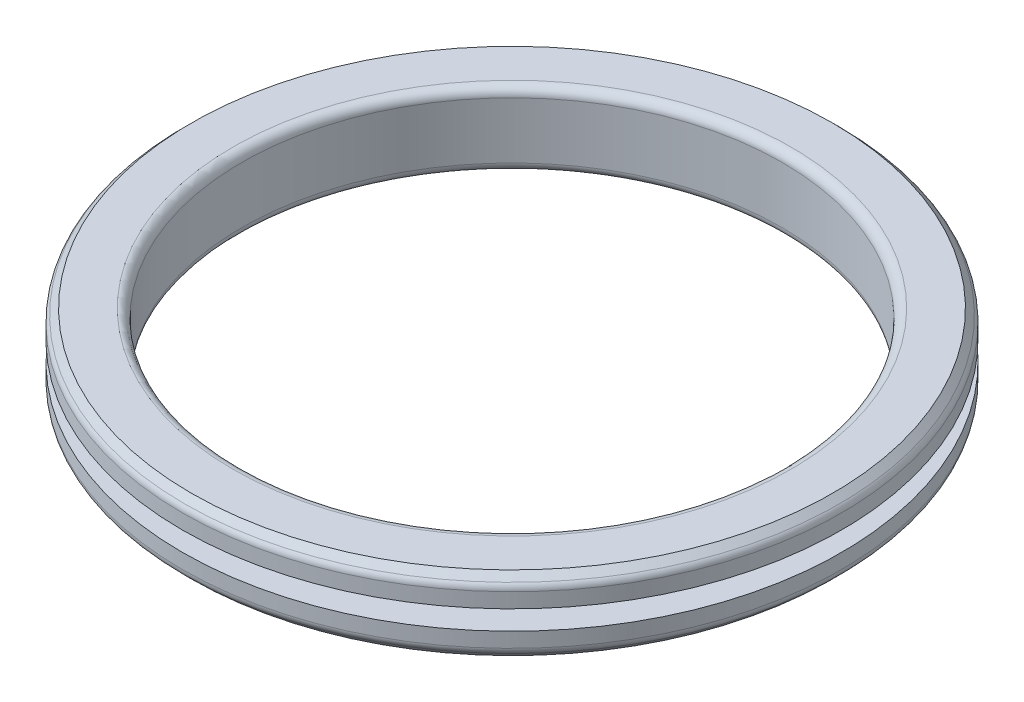
SolidWorks part; units mm, degrees
material "Titanium Ti-8Mn, Annealed"
ref_plane "Front Plane" through (0, 0, 0) normal (0, 0, 1) x (1, 0, 0)
ref_plane "Top Plane" through (0, 0, 0) normal (0, 1, 0) x (1, 0, 0)
ref_plane "Right Plane" through (0, 0, 0) normal (1, 0, 0) x (0, 0, -1)
sketch "Sketch1" plane through (0, 0, 0) normal (0, 1, 0) x (1, 0, 0)
  circle A0 centre (0, 0) radius 9.1
  circle A1 centre (0, 0) radius 11.1
  dimension "D1" = 18.2
  dimension "D2" = 2
extrude "Boss-Extrude1" add sketch "Sketch1" along normal blind 2.5
chamfer "Chamfer1" distance 0.3 angle 45 2 edges at (0, 0, 11.1) (0, 2.5, 11.1)
fillet "Fillet1" radius 0.3 2 edges at (0, 0, 9.1) (0, 2.5, 9.1)
fillet "Fillet2" radius 0.3 2 edges at (0, 2.2, 11.1) (0, 0.3, 11.1)
sketch "Sketch7" plane through (0, 0, 0) normal (1, 0, 0) x (0, 0, -1)
  line L0 (0, -4.2926) -> (0, 12.7354) construction
  line L1 (-12.0412, 1.5757) -> (-10.1, 1.5757)
  line L2 (-12.0412, 1.5757) -> (-12.0412, 0.9243)
  line L3 (-12.0412, 0.9243) -> (-10.1, 0.9243)
  line L4 (-10.1, 1.5757) -> (-10.1, 0.9243)
  line L5 (-12.0412, 1.5757) -> (-10.1, 0.9243) construction
  line L6 (-12.0412, 0.9243) -> (-10.1, 1.5757) construction
  line L7 (-11.1, 2.0757) -> (-11.1, 0.4243) construction
  line L10 (11.1, 0.4243) -> (-11.1, 0.4243) construction
  line L11 (-11.1, 2.0757) -> (11.1, 2.0757) construction
  point P0 (-11.0706, 1.25)
  dimension "D1" = 1
  dimension "D2" = 0.5
  dimension "D3" = 0.5
revolve "Cut-Revolve3" cut sketch "Sketch7" angle 360 about L0
